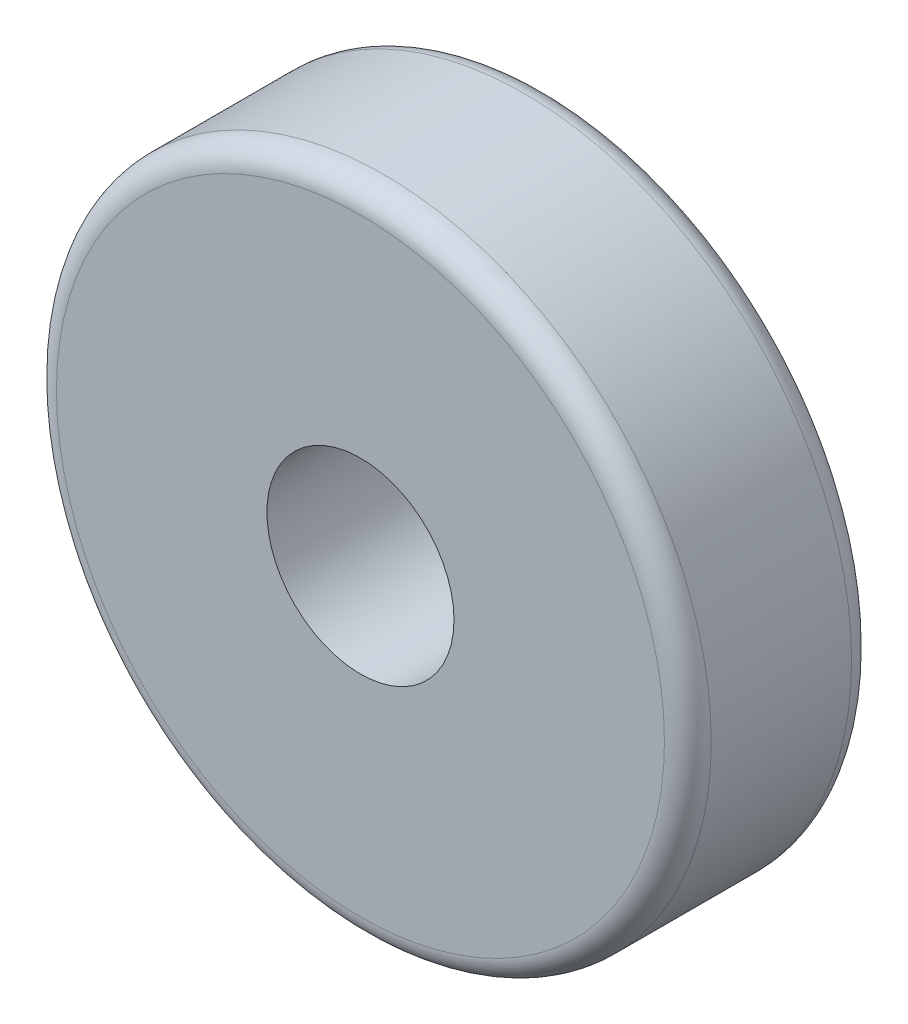
SolidWorks part; units mm, degrees
material "6063-T1"
ref_plane "前视基准面" through (0, 0, 0) normal (0, 0, 1) x (1, 0, 0)
ref_plane "上视基准面" through (0, 0, 0) normal (0, 1, 0) x (1, 0, 0)
ref_plane "右视基准面" through (0, 0, 0) normal (1, 0, 0) x (0, 0, -1)
other "Configuration Table"
sketch "草图1" plane through (0, 0, 0) normal (0, 0, 1) x (1, 0, 0)
  circle A0 centre (0, 0) radius 2
  circle A1 centre (0, 0) radius 7
  dimension "D1" = 4
  dimension "D2" = 14
extrude "凸台-拉伸1" add sketch "草图1" along normal blind 4
fillet "圆角1" radius 0.5 2 edges at (7, 0, 0) (7, 0, 4)
